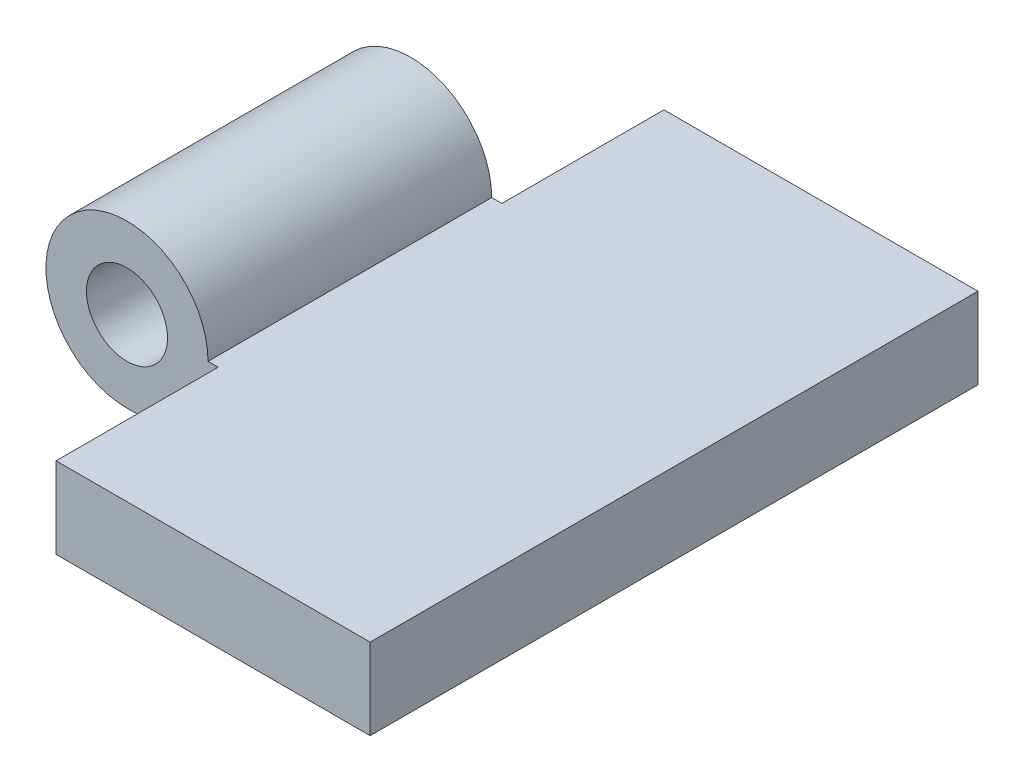
SolidWorks part; units mm, degrees
ref_plane "前视基准面" through (0, 0, 0) normal (0, 0, 1) x (1, 0, 0)
ref_plane "上视基准面" through (0, 0, 0) normal (0, 1, 0) x (1, 0, 0)
ref_plane "右视基准面" through (0, 0, 0) normal (1, 0, 0) x (0, 0, -1)
sketch "草图1" plane through (0, 0, 0) normal (0, 0, 1) x (1, 0, 0)
  line L1 (4, 0) -> (20, 0)
  line L3 (0, -4) -> (20, -4)
  line L4 (20, 0) -> (20, -4)
  arc A0 (4, 0) -> (0, -4) centre (0, 0) ccw
  dimension "D1" = 20
  dimension "D2" = 4
extrude "凸台-拉伸1" add sketch "草图1" along normal blind 30
sketch "草图2" plane through (0, -4, 0) normal (0, -1, 0) x (1, 0, 0)
  line L0 (0, 30) -> (0, 0) construction
  line L7 (4, 30) -> (-4, 30) construction
  line L9 (-4.5, 22) -> (4.5, 22)
  line L10 (-4.5, 22) -> (-4.5, 30.9378)
  line L11 (-4.5, 30.9378) -> (4.5, 30.9378)
  line L12 (4.5, 22) -> (4.5, 30.9378)
  line L13 (-4.5, 8) -> (4.5, 8)
  line L14 (-4.5, 8) -> (-4.5, -2.0679)
  line L15 (-4.5, -2.0679) -> (4.5, -2.0679)
  line L16 (4.5, 8) -> (4.5, -2.0679)
  point P0 (0, 15)
  point P13 (0, 0)
  dimension "D1" = 14
  dimension "D2" = 9
  dimension "D3" = 15
extrude "切除-拉伸1" cut sketch "草图2" against normal blind 15
sketch "草图3" plane through (0, 0, 0) normal (0, 0, -1) x (-1, 0, 0)
  circle A0 centre (0, 0) radius 2
extrude "切除-拉伸2" cut sketch "草图3" against normal blind 32
